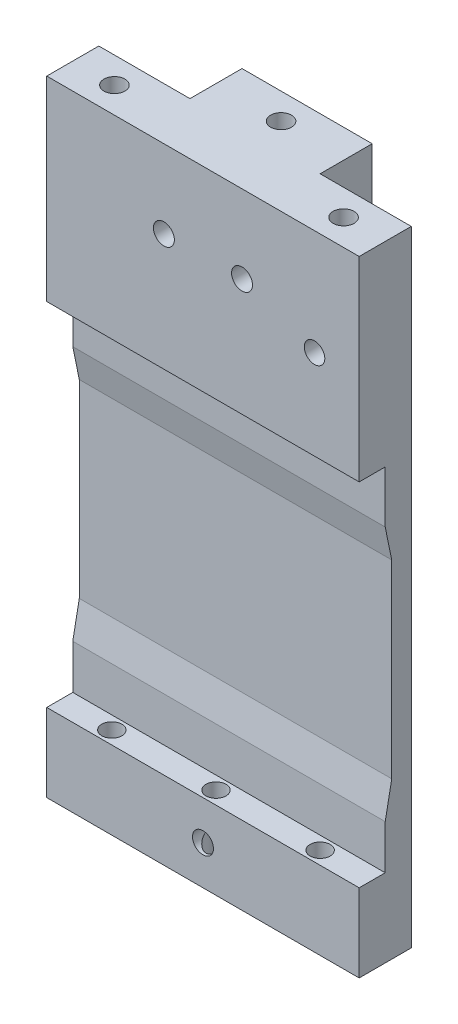
SolidWorks part; units mm, degrees
material "6061 Alloy"
ref_plane "Front Plane" through (0, 0, 0) normal (0, 0, 1) x (1, 0, 0)
ref_plane "Top Plane" through (0, 0, 0) normal (0, 1, 0) x (1, 0, 0)
ref_plane "Right Plane" through (0, 0, 0) normal (1, 0, 0) x (0, 0, -1)
sketch "Sketch1" plane through (0, 0, 0) normal (0, 1, 0) x (1, 0, 0)
  line L0 (-15.875, 6.35) -> (-15.875, 19.05)
  line L1 (38.1, -6.35) -> (-38.1, -6.35)
  line L2 (38.1, -6.35) -> (38.1, 6.35)
  line L3 (38.1, 6.35) -> (15.875, 6.35)
  line L4 (-38.1, -6.35) -> (-38.1, 6.35)
  line L5 (38.1, -6.35) -> (-38.1, 6.35) construction
  line L6 (38.1, 6.35) -> (-38.1, -6.35) construction
  line L7 (-15.875, 19.05) -> (15.875, 19.05)
  line L8 (15.875, 19.05) -> (15.875, 6.35)
  line L9 (-15.875, 6.35) -> (-38.1, 6.35)
  line L10 (0, 19.05) -> (0, 0) construction
  point P0 (0, 0)
  dimension "D1" = 76.2
  dimension "D2" = 12.7
  dimension "D3" = 31.75
  dimension "D4" = 12.7
extrude "Boss-Extrude1" add sketch "Sketch1" along normal mid plane 152.4
ref_plane "Plane1" through (0, 0, 0) normal (0, 1, 0) x (1, 0, 0)
sketch "Sketch5" plane through (0, 0, 0) normal (0, 1, 0) x (1, 0, 0)
  line L0 (-4.7625, 19.05) -> (-4.7625, 12.7)
  line L1 (15.875, 19.05) -> (-15.875, 19.05) construction
  line L2 (4.7625, 12.7) -> (4.7625, 19.05)
  line L3 (0, 0) -> (0, 12.7) construction
  line L4 (-4.7625, 19.05) -> (4.7625, 19.05)
  arc A0 (-4.7625, 12.7) -> (4.7625, 12.7) centre (0, 12.7) ccw
  point P10 (0, 7.9375)
  dimension "D1" = 11.1125
  dimension "D2" = 9.525
extrude "Cut-Extrude3" cut sketch "Sketch5" against normal mid plane 95.25
sketch "Sketch9" plane through (0, 0, 0) normal (1, 0, 0) x (0, 0, -1)
  line L0 (19.05, -52.3875) -> (12.7, -52.3875)
  line L1 (19.05, -52.3875) -> (19.05, -47.625)
  line L2 (19.05, -47.625) -> (7.9375, -47.625) construction
  line L3 (12.7, -52.3875) -> (12.7, -47.625) construction
  line L4 (7.9375, -47.625) -> (19.05, -47.625)
  arc A0 (12.7, -52.3875) -> (7.9375, -47.625) centre (12.7, -47.625) cw
  dimension "D2" = 90
  dimension "D1" = 4.7625
  dimension "D3" = 11.1125
revolve "Cut-Revolve1" cut sketch "Sketch9" angle 360 about L4
mirror "Mirror1" about plane through (0, 0, 0) normal (0, 1, 0) of "Cut-Revolve1"
ref_plane "Parting Plane" through (0, 0, 0) normal (0, 0, 1) x (1, 0, 0)
sketch "Sketch12" plane through (38.1, 0, 0) normal (1, 0, 0) x (0, 0, -1)
  line L0 (-6.35, -57.15) -> (0, -57.15)
  line L1 (-6.35, 76.2) -> (-6.35, -76.2) construction
  line L2 (0, 45.4834) -> (0, -45.4834) construction
  line L3 (0, -57.15) -> (0, -46.3437)
  line L4 (0, -46.3437) -> (1.5875, -38.1)
  line L5 (1.5875, -38.1) -> (1.5875, 8.129)
  line L6 (1.5875, 8.129) -> (0, 15.875)
  line L7 (0, 15.875) -> (0, 28.575)
  line L8 (0, 28.575) -> (-6.35, 28.575)
  line L9 (-6.35, 28.575) -> (-6.35, -57.15)
  line L11 (-6.35, 76.2) -> (6.35, 76.2) construction
  dimension "D1" = 19.05
  dimension "D2" = 47.625
  dimension "D3" = 85.725
  dimension "D4" = 1.5875
  dimension "D5" = 12.7
extrude "Cut-Extrude4" cut sketch "Sketch12" against normal through all
hole_wizard "#10 (0.1935) Diameter Hole1" positions "Sketch15" profile "Sketch16" hole size "#10" standard "ANSI Inch"
sketch "Sketch15" plane through (0, -76.2, 0) normal (0, -1, 0) x (-1, 0, 0)
  line L0 (38.1, 6.35) -> (38.1, -6.35) construction
  line L1 (-38.1, -6.35) -> (-38.1, 6.35) construction
  line L3 (25.4, -3.175) -> (-25.4, -3.175) construction
  line L4 (38.1, -6.35) -> (-38.1, -6.35) construction
  point P0 (25.4, -3.175)
  point P2 (-25.4, -3.175)
  point P16 (0, -3.175)
  dimension "D1" = 12.7
  dimension "D2" = 12.7
  dimension "D3" = 3.175
sketch "Sketch16" plane through (-25.4, -76.2, 3.175) normal (1, 0, 0) x (0, 0, -1)
  line L0 (0, 0) -> (0, 20.5266)
  line L1 (0, 20.5266) -> (2.4574, 19.05)
  line L2 (2.4574, 19.05) -> (2.4574, 0)
  line L5 (2.4574, 0) -> (0, 0)
  line L10 (0, 20.5266) -> (-2.4575, 19.05) construction
  line L11 (0, -6.35) -> (0, 107.95) construction
  dimension "Hole Dia." = 4.9149
  dimension "Hole Depth" = 19.05
  dimension "Drill Angle" = 118
hole_wizard "1/4-20 Tapped Hole1" positions "Sketch17" profile "Sketch18" tap size "1/4-20" standard "ANSI Inch" end condition through all
sketch "Sketch17" plane through (0, 76.2, 0) normal (0, 1, 0) x (1, 0, 0)
  line L0 (15.875, 19.05) -> (-15.875, 19.05) construction
  line L1 (15.875, 6.35) -> (15.875, 19.05) construction
  point P0 (0, 12.7)
  dimension "D1" = 6.35
  dimension "D2" = 15.875
sketch "Sketch18" plane through (0, 76.2, -12.7) normal (1, 0, 0) x (0, 0, 1)
  line L0 (0, 0) -> (0, 152.4)
  line L1 (0, 152.4) -> (2.5527, 152.4)
  line L2 (2.5527, 152.4) -> (2.5527, 0)
  line L5 (2.5527, 0) -> (0, 0)
  line L11 (0, -6.35) -> (0, 107.95) construction
  dimension "Thru Tap Drill Dia." = 5.1054
  dimension "Thru Tap Drill Depth" = 152.4
cosmetic thread "Hole Thread1" parameters "D2"=6.35
sketch "Sketch19" plane through (0, 0, -6.35) normal (0, 0, -1) x (-1, 0, 0)
  circle A0 centre (-27.209, 50.4369) radius 2.5
  point P2 (-27.1921, 56.4495)
  point P3 (-26.9875, 53.9569)
  point P4 (-27.4455, 49.8908)
  point P5 (0, 0)
  point P6 (0, 0)
  point P7 (-28.3761, 49.4878)
  point P8 (-26.9875, 46.4569)
  point P9 (-26.9875, 48.9569)
  point P10 (-27.209, 49.4183)
  point P12 (-26.9875, 56.4569)
  dimension "D1" = 5
extrude "Cut-Extrude5" cut sketch "Sketch19" against normal through all
hole_wizard "1/4-20 Tapped Hole2" positions "Sketch20" profile "Sketch21" tap size "1/4-20" standard "ANSI Inch"
sketch "Sketch20" plane through (0, 76.2, 0) normal (0, 1, 0) x (1, 0, 0)
  point P0 (27.94, 0)
  point P3 (-27.94, 0)
sketch "Sketch21" plane through (27.94, 76.2, 0) normal (1, 0, 0) x (0, 0, 1)
  line L0 (0, 0) -> (0, 41.0638)
  line L1 (0, 41.0638) -> (2.5527, 39.53)
  line L2 (2.5527, 39.53) -> (2.5527, 0)
  line L5 (2.5527, 0) -> (0, 0)
  line L10 (0, 41.0638) -> (-2.5527, 39.53) construction
  line L11 (0, -6.35) -> (0, 107.95) construction
  dimension "Tap Drill Dia." = 5.1054
  dimension "Tap Drill Depth" = 39.53
  dimension "Drill Angle" = 118
cosmetic thread "Hole Thread2" parameters "D1"=95.25, "D2"=6.35
cosmetic thread "Hole Thread3" parameters "D1"=95.25, "D2"=6.35
hole_wizard "1/4-20 Tapped Hole3" positions "Sketch22" profile "Sketch23" tap size "1/4-20" standard "ANSI Inch"
sketch "Sketch22" plane through (0, 0, -19.05) normal (0, 0, -1) x (-1, 0, 0)
  line L0 (9.525, 57.15) -> (-9.525, 57.15) construction
  line L2 (0, 57.15) -> (0, 0) construction
  line L4 (-15.875, -76.2) -> (15.875, -76.2) construction
  point P0 (0, -66.675)
  point P2 (9.525, 57.15)
  point P4 (-9.525, 57.15)
  dimension "D1" = 19.05
  dimension "D2" = 123.825
  dimension "D3" = 9.525
sketch "Sketch23" plane through (0, -66.675, -19.05) normal (1, 0, 0) x (0, 1, 0)
  line L0 (0, 0) -> (0, 43.6038)
  line L1 (0, 43.6038) -> (2.5527, 42.07)
  line L2 (2.5527, 42.07) -> (2.5527, 0)
  line L5 (2.5527, 0) -> (0, 0)
  line L10 (0, 43.6038) -> (-2.5527, 42.07) construction
  line L11 (0, -6.35) -> (0, 107.95) construction
  dimension "Tap Drill Dia." = 5.1054
  dimension "Tap Drill Depth" = 42.07
  dimension "Drill Angle" = 118
cosmetic thread "Hole Thread4" parameters "D1"=38.26, "D2"=6.35
cosmetic thread "Hole Thread5" parameters "D1"=38.26, "D2"=6.35
cosmetic thread "Hole Thread6" parameters "D1"=38.26, "D2"=6.35
